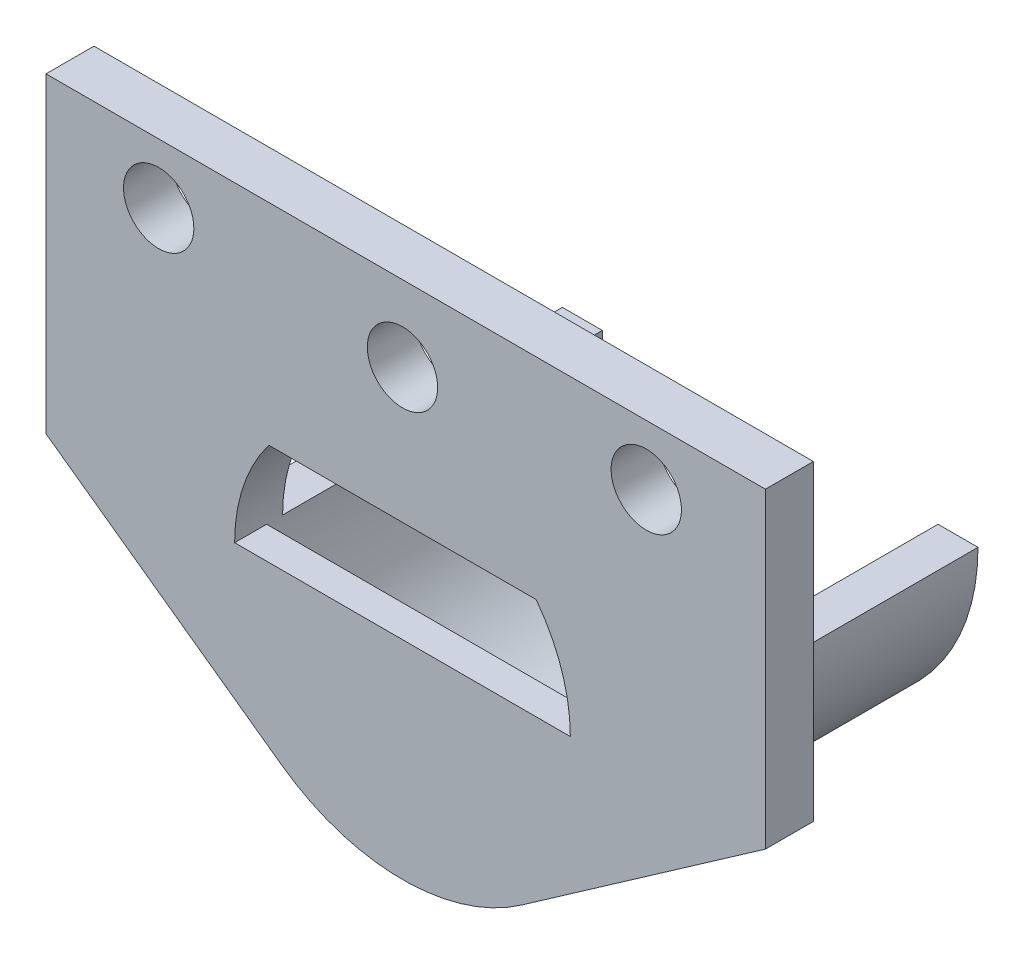
SolidWorks part; units mm, degrees
ref_plane "前视基准面" through (0, 0, 0) normal (0, 0, 1) x (1, 0, 0)
ref_plane "上视基准面" through (0, 0, 0) normal (0, 1, 0) x (1, 0, 0)
ref_plane "右视基准面" through (0, 0, 0) normal (1, 0, 0) x (0, 0, -1)
other "Configuration Table"
sketch "草图2" plane through (0, 0, 0) normal (0, 0, 1) x (1, 0, 0)
  line L5 (8214.6708, 3013.1134) -> (8259.6708, 3013.1134)
  line L6 (8214.6708, 3013.1134) -> (8214.6708, 2993.6134)
  line L8 (8259.6708, 3013.1134) -> (8259.6708, 2993.6134)
  line L10 (8214.6708, 2993.6134) -> (8229.3912, 2983.0515)
  line L11 (8259.6708, 2993.6134) -> (8244.4133, 2982.9563)
  circle A0 centre (8236.9694, 2993.6134) radius 10.5
  arc A2 (8229.3912, 2983.0515) -> (8244.4133, 2982.9563) centre (8236.9694, 2993.6134) ccw
  circle A4 centre (8236.9694, 3008.3663) radius 2.2
  circle A5 centre (8221.7194, 3009.3663) radius 2.2
  circle A6 centre (8252.2194, 3009.3663) radius 2.2
  dimension "D8" = 30.5
  dimension "D1" = 45
extrude "凸台-拉伸1" add sketch "草图2" along normal blind 3
sketch "草图3" plane through (0, 0, 3) normal (0, 0, 1) x (1, 0, 0)
  line L0 (8247.4694, 2993.6134) -> (8226.4694, 2993.6134)
  line L1 (8228.6079, 2999.9643) -> (8245.331, 2999.9643)
  arc A0 (8226.4694, 2993.6134) -> (8247.4694, 2993.6134) centre (8236.9694, 2993.6134) ccw
  arc A1 (8245.331, 2999.9643) -> (8228.6079, 2999.9643) centre (8236.9694, 2993.6134) ccw
extrude "凸台-拉伸3" add sketch "草图3" against normal blind 2
sketch "草图5" plane through (0, 0, 0) normal (0, 0, -1) x (-1, 0, 0)
  line L0 (-8247.4694, 2993.6134) -> (-8226.4694, 2993.6134) construction
  line L1 (-8247.4694, 2993.6134) -> (-8249.9689, 2993.6134)
  line L2 (-8226.4694, 2993.6134) -> (-8223.97, 2993.6134)
  arc A0 (-8247.4694, 2993.6134) -> (-8226.4694, 2993.6134) centre (-8236.9694, 2993.6134) ccw
  arc A1 (-8249.9689, 2993.6134) -> (-8223.97, 2993.6134) centre (-8236.9694, 2993.6134) ccw
extrude "凸台-拉伸5" add sketch "草图5" along normal blind 20
